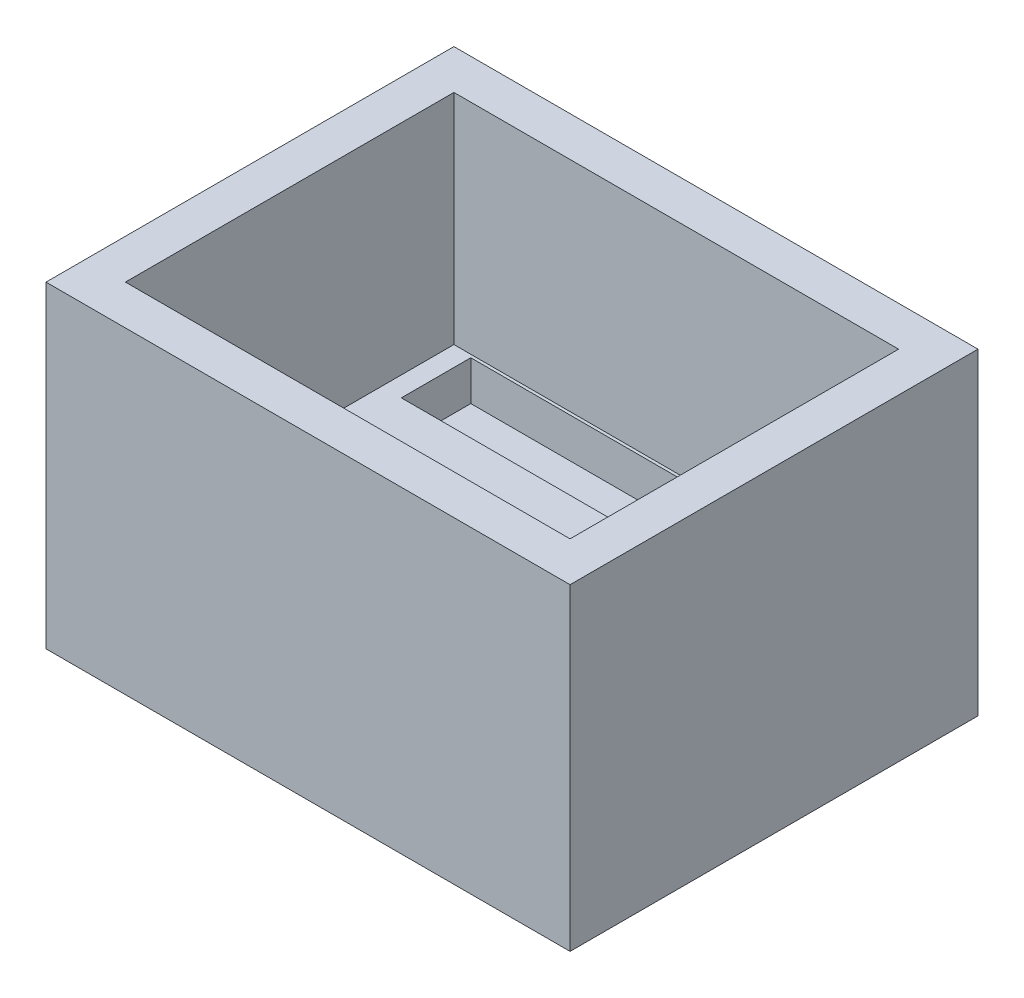
SolidWorks part; units mm, degrees
ref_plane "Front Plane" through (0, 0, 0) normal (0, 0, 1) x (1, 0, 0)
ref_plane "Top Plane" through (0, 0, 0) normal (0, 1, 0) x (1, 0, 0)
ref_plane "Right Plane" through (0, 0, 0) normal (1, 0, 0) x (0, 0, -1)
sketch "Sketch1" plane through (0, 0, 0) normal (0, 1, 0) x (1, 0, 0)
  line L0 (-11.2, -7.075) -> (11.622, -7.075) construction
  line L1 (-10.2, 8.275) -> (10.2, 8.275)
  line L2 (-10.2, 8.275) -> (-10.2, -8.275)
  line L3 (-10.2, -8.275) -> (10.2, -8.275)
  line L4 (10.2, 8.275) -> (10.2, -8.275)
  line L5 (-10.2, 8.275) -> (10.2, -8.275) construction
  line L6 (-10.2, -8.275) -> (10.2, 8.275) construction
  line L7 (-9.2, 7.8041) -> (-9.2, -9.3368) construction
  line L8 (9.2, -9.3368) -> (9.2, 8.1722) construction
  line L9 (-10.2, 8.275) -> (-11.2, 8.275)
  line L10 (-11.2, 8.275) -> (-11.2, -8.275)
  line L11 (-11.2, -8.275) -> (-10.2, -8.275)
  line L12 (10.2, -8.275) -> (11.2, -8.275)
  line L13 (11.2, -8.275) -> (11.2, 8.275)
  line L14 (11.2, 8.275) -> (10.2, 8.275)
  circle A0 centre (-7.65, -5.525) radius 1.55
  circle A1 centre (7.65, -5.525) radius 1.55
  point P0 (0, 0)
  dimension "D2" = 3.1
  dimension "D1" = 20.4
  dimension "D3" = 1.2
  dimension "D4" = 1
  dimension "D5" = 1
  dimension "D6" = 16.55
  dimension "D7" = 1
  dimension "D8" = 1
extrude "Boss-Extrude1" add sketch "Sketch1" along normal blind 5 contours A0 | A1 | L10 L11 L2 L9 | L13 L14 L4 L12
sketch "Sketch2" plane through (0, 5, 0) normal (0, 1, 0) x (1, 0, 0)
  line L1 (-10.2, 8.125) -> (10.2, 8.125)
  line L2 (-10.2, 8.125) -> (-10.2, 4.625)
  line L3 (-10.2, 4.625) -> (10.2, 4.625)
  line L4 (10.2, 8.125) -> (10.2, 4.625)
  line L5 (-11.2, 8.275) -> (-11.2, -8.275) construction
  line L6 (11.2, -8.275) -> (11.2, 8.275) construction
  line L7 (-11.2, -8.275) -> (11.2, -8.275) construction
  dimension "D1" = 3.5
  dimension "D2" = 1
  dimension "D3" = 1
  dimension "D4" = 12.9
extrude "Cut-Extrude1" cut sketch "Sketch2" against normal blind 2
sketch "Sketch3" plane through (0, 0, 0) normal (0, -1, 0) x (1, 0, 0)
  line L4 (-13.2, 10.275) -> (-13.2, -10.275)
  line L5 (-13.2, -10.275) -> (13.2, -10.275)
  line L6 (13.2, -10.275) -> (13.2, 10.275)
  line L7 (13.2, 10.275) -> (-13.2, 10.275)
  line L8 (-11.2, 8.275) -> (-11.2, -8.275)
  line L9 (-11.2, -8.275) -> (11.2, -8.275)
  line L10 (11.2, -8.275) -> (11.2, 8.275)
  line L11 (11.2, 8.275) -> (-11.2, 8.275)
  line L12 (-11.2, 8.275) -> (-11.2, -8.275)
  line L13 (-11.2, -8.275) -> (11.2, -8.275)
  line L14 (11.2, -8.275) -> (11.2, 8.275)
  line L15 (11.2, 8.275) -> (-11.2, 8.275)
  dimension "D1" = 0
  dimension "D2" = 2
extrude "Boss-Extrude2" add sketch "Sketch3" against normal blind 16
sketch "Sketch4" plane through (11.2, 0, 0) normal (-1, 0, 0) x (0, 0, 1)
  line L0 (-7.2603, 14.0395) -> (-5.5041, 6.3081)
  line L1 (-5.5041, 6.3081) -> (-4.369, 6.3081)
  line L2 (-4.369, 6.3081) -> (-6.1252, 14.0395)
  line L3 (-6.1252, 14.0395) -> (-7.2603, 14.0395)
  line L4 (-4.1252, 14.0395) -> (-5.2603, 14.0395)
  line L5 (-5.2603, 14.0395) -> (-3.5041, 6.3081)
  line L6 (-3.5041, 6.3081) -> (-2.369, 6.3081)
  line L7 (-2.369, 6.3081) -> (-4.1252, 14.0395)
  line L8 (-2.1252, 14.0395) -> (-3.2603, 14.0395)
  line L9 (-3.2603, 14.0395) -> (-1.5041, 6.3081)
  line L10 (-1.5041, 6.3081) -> (-0.369, 6.3081)
  line L11 (-0.369, 6.3081) -> (-2.1252, 14.0395)
  line L12 (-0.1252, 14.0395) -> (-1.2603, 14.0395)
  line L13 (-1.2603, 14.0395) -> (0.4959, 6.3081)
  line L14 (0.4959, 6.3081) -> (1.631, 6.3081)
  line L15 (1.631, 6.3081) -> (-0.1252, 14.0395)
  line L16 (1.8748, 14.0395) -> (0.7397, 14.0395)
  line L17 (0.7397, 14.0395) -> (2.4959, 6.3081)
  line L18 (2.4959, 6.3081) -> (3.631, 6.3081)
  line L19 (3.631, 6.3081) -> (1.8748, 14.0395)
  line L20 (3.8748, 14.0395) -> (2.7397, 14.0395)
  line L21 (2.7397, 14.0395) -> (4.4959, 6.3081)
  line L22 (4.4959, 6.3081) -> (5.631, 6.3081)
  line L23 (5.631, 6.3081) -> (3.8748, 14.0395)
  line L24 (5.8748, 14.0395) -> (4.7397, 14.0395)
  line L25 (4.7397, 14.0395) -> (6.4959, 6.3081)
  line L26 (6.4959, 6.3081) -> (7.631, 6.3081)
  line L27 (7.631, 6.3081) -> (5.8748, 14.0395)
  dimension "D1" = 7
extrude "Cut-Extrude2" [suppressed] cut sketch "Sketch4" against normal through all both and the other way through all contours L6 L7 L4 L5 | L10 L11 L8 L9 | L14 L15 L12 L13 | L22 L23 L20 L21 | L26 L27 L24 L25 | L3 L0 L1 L2 | L19 L16 L17 L18
